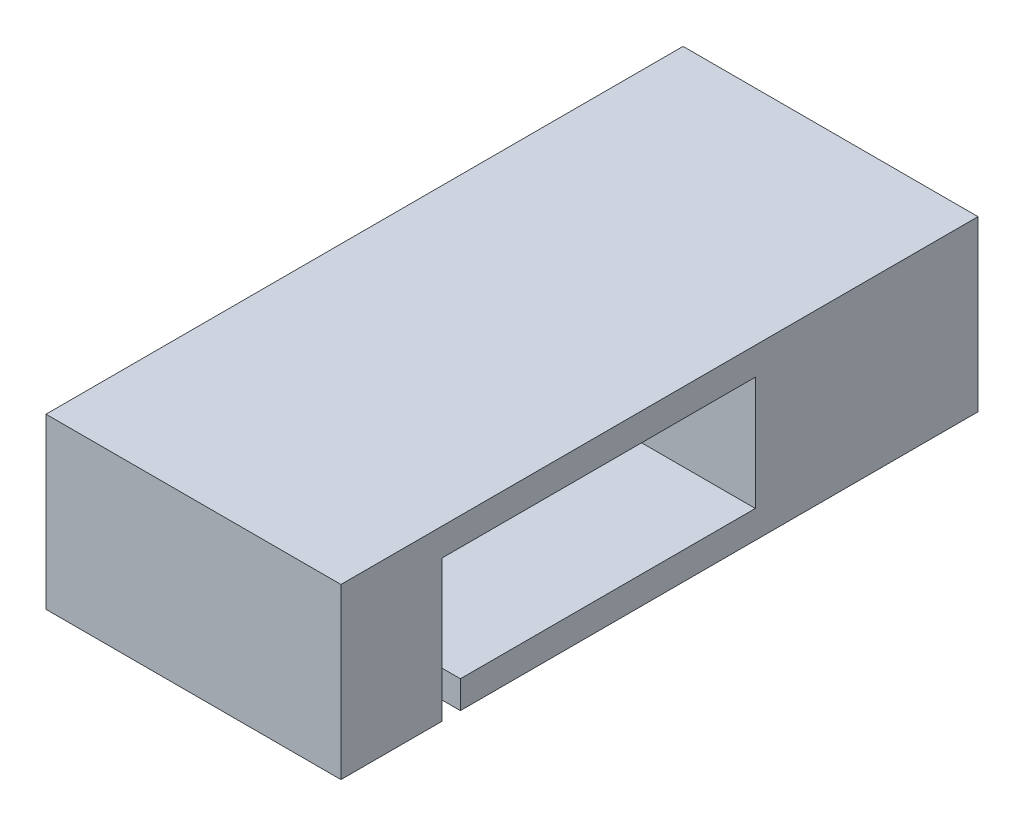
SolidWorks part; units mm, degrees
ref_plane "Front Plane" through (0, 0, 0) normal (0, 0, 1) x (1, 0, 0)
ref_plane "Top Plane" through (0, 0, 0) normal (0, 1, 0) x (1, 0, 0)
ref_plane "Right Plane" through (0, 0, 0) normal (1, 0, 0) x (0, 0, -1)
sketch "Sketch2" plane through (0, 0, 0) normal (0, 1, 0) x (1, 0, 0)
  line L1 (-16, -34.56) -> (16, -34.56)
  line L2 (-16, -34.56) -> (-16, 34.56)
  line L3 (-16, 34.56) -> (16, 34.56)
  line L4 (16, -34.56) -> (16, 34.56)
  line L5 (-16, -34.56) -> (16, 34.56) construction
  line L6 (-16, 34.56) -> (16, -34.56) construction
  point P0 (0, 0)
  dimension "D1" = 32
  dimension "D2" = 69.12
extrude "Boss-Extrude1" add sketch "Sketch2" along normal blind 18.34
sketch "Sketch3" plane through (16, 0, 0) normal (1, 0, 0) x (0, 0, -1)
  line L0 (-34.56, 18.34) -> (34.56, 18.34) construction
  line L1 (-23.6, 15.34) -> (10.4, 15.34)
  line L2 (-23.6, 15.34) -> (-23.6, 3)
  line L4 (10.4, 15.34) -> (10.4, 3)
  line L5 (-23.6, 15.34) -> (10.4, 3) construction
  line L6 (-23.6, 3) -> (10.4, 15.34) construction
  line L7 (-34.56, 0) -> (34.56, 0) construction
  line L8 (-23.6, 3) -> (-23.6, 0)
  line L9 (-23.6, 0) -> (-21.6, 0)
  line L10 (-21.6, 0) -> (-21.6, 3)
  line L11 (-21.6, 3) -> (10.4, 3)
  circle A0 centre (0, 9.17) radius 2.305 construction
  point P2 (-6.6, 9.17)
  point P12 (-23.6, 9.17)
  point P18 (10.4, 9.17)
  dimension "D1" = 3
  dimension "D5" = 4.61
  dimension "D2" = 32
  dimension "D3" = 34
  dimension "D4" = 10.4
  dimension "D6" = 2
  dimension "D7" = 3
extrude "Cut-Extrude1" cut sketch "Sketch3" against normal blind 29
sketch "Sketch4" plane through (-16, 0, 0) normal (-1, 0, 0) x (0, 0, 1)
  circle A0 centre (0, 9.17) radius 2.305
  dimension "D1" = 4.61
extrude "Boss-Extrude3" add sketch "Sketch4" along normal blind 6
